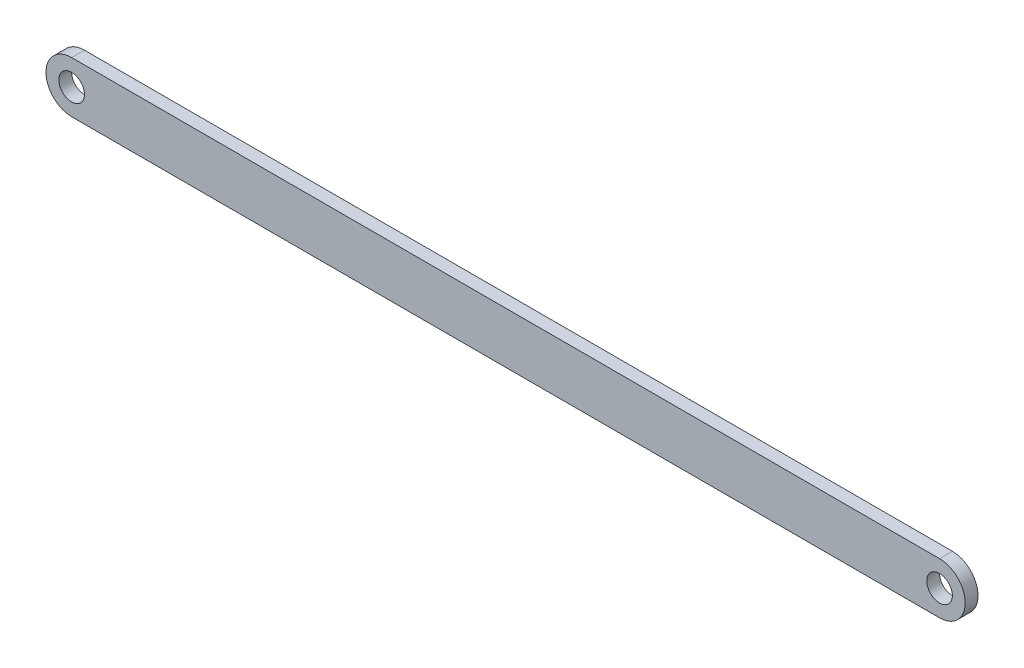
SolidWorks part; units mm, degrees
ref_plane "Plano frontal" through (0, 0, 0) normal (0, 0, 1) x (1, 0, 0)
ref_plane "Plano superior" through (0, 0, 0) normal (0, 1, 0) x (1, 0, 0)
ref_plane "Plano direito" through (0, 0, 0) normal (1, 0, 0) x (0, 0, -1)
sketch "Esboço1" plane through (0, 0, 0) normal (0, 0, 1) x (1, 0, 0)
  line L0 (-33.855, 2) -> (33.855, 2)
  line L1 (-33.855, 0) -> (33.855, 0) construction
  line L2 (-33.855, -2) -> (33.855, -2)
  arc A0 (-33.855, 2) -> (-33.855, -2) centre (-33.855, 0) ccw
  arc A1 (33.855, 2) -> (33.855, -2) centre (33.855, 0) cw
  circle A2 centre (-33.855, 0) radius 1
  circle A3 centre (33.855, 0) radius 1
  point P3 (0, 2)
  dimension "D2" = 2
  dimension "D1" = 67.71
  dimension "D3" = 2
extrude "Ressalto-extrusão1" add sketch "Esboço1" along normal blind 1
